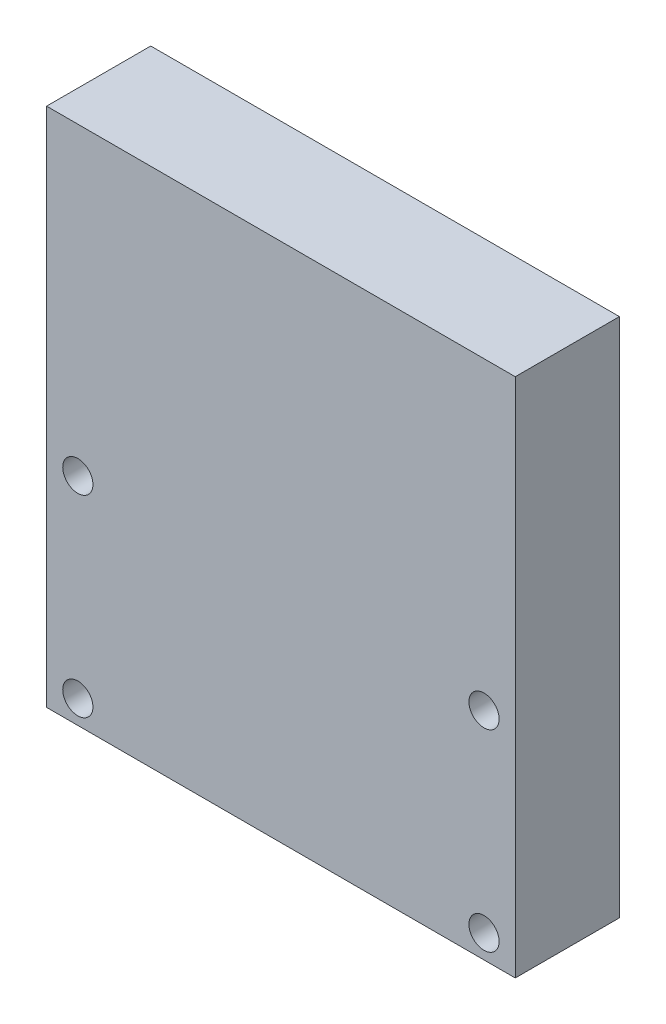
SolidWorks part; units mm, degrees
ref_plane "Front Plane" through (0, 0, 0) normal (0, 0, 1) x (1, 0, 0)
ref_plane "Top Plane" through (0, 0, 0) normal (0, 1, 0) x (1, 0, 0)
ref_plane "Right Plane" through (0, 0, 0) normal (1, 0, 0) x (0, 0, -1)
sketch "Sketch2" plane through (0, 0, 0) normal (0, 1, 0) x (1, 0, 0)
  line L1 (22.5, 5) -> (-22.5, 5)
  line L2 (22.5, 5) -> (22.5, -5)
  line L3 (22.5, -5) -> (-22.5, -5)
  line L4 (-22.5, 5) -> (-22.5, -5)
  line L5 (22.5, 5) -> (-22.5, -5) construction
  line L6 (22.5, -5) -> (-22.5, 5) construction
  point P0 (0, 0)
  dimension "D1" = 10
  dimension "D2" = 45
extrude "Boss-Extrude1" add sketch "Sketch2" along normal blind 40
sketch "Sketch3" plane through (0, 0, -5) normal (0, 0, -1) x (-1, 0, 0)
  line L0 (0, 0) -> (0, 40) construction
  line L1 (-22.5, 40) -> (22.5, 40) construction
  line L3 (22.5, 40) -> (22.5, 0) construction
  line L4 (-22.5, 40) -> (-22.5, 0) construction
  line L5 (-22.5, 0) -> (22.5, 0) construction
  line L6 (-22.5, 11.5) -> (22.5, 11.5) construction
  circle A0 centre (19.5, 2.25) radius 1.45
  circle A3 centre (-19.5, 2.25) radius 1.45
  circle A4 centre (-19.5, 20.75) radius 1.45
  circle A5 centre (19.5, 20.75) radius 1.45
  dimension "D3" = 2.9
  dimension "D4" = 3
  dimension "D1" = 3
  dimension "D2" = 2.25
extrude "Cut-Extrude1" cut sketch "Sketch3" against normal blind 40
sketch "Sketch4" plane through (0, 40, 0) normal (0, 1, 0) x (1, 0, 0)
  line L1 (-22.5, 5) -> (22.5, 5)
  line L2 (-22.5, 5) -> (-22.5, -5)
  line L3 (-22.5, -5) -> (22.5, -5)
  line L4 (22.5, 5) -> (22.5, -5)
extrude "Boss-Extrude2" add sketch "Sketch4" along normal blind 10
sketch "Sketch6" plane through (0, 0, -5) normal (0, 0, -1) x (-1, 0, 0)
  line L2 (-22.5, 23) -> (22.7712, 23) construction
  circle A1 centre (-19.5, 20.75) radius 1.45 construction
  dimension "D1" = 2.25
